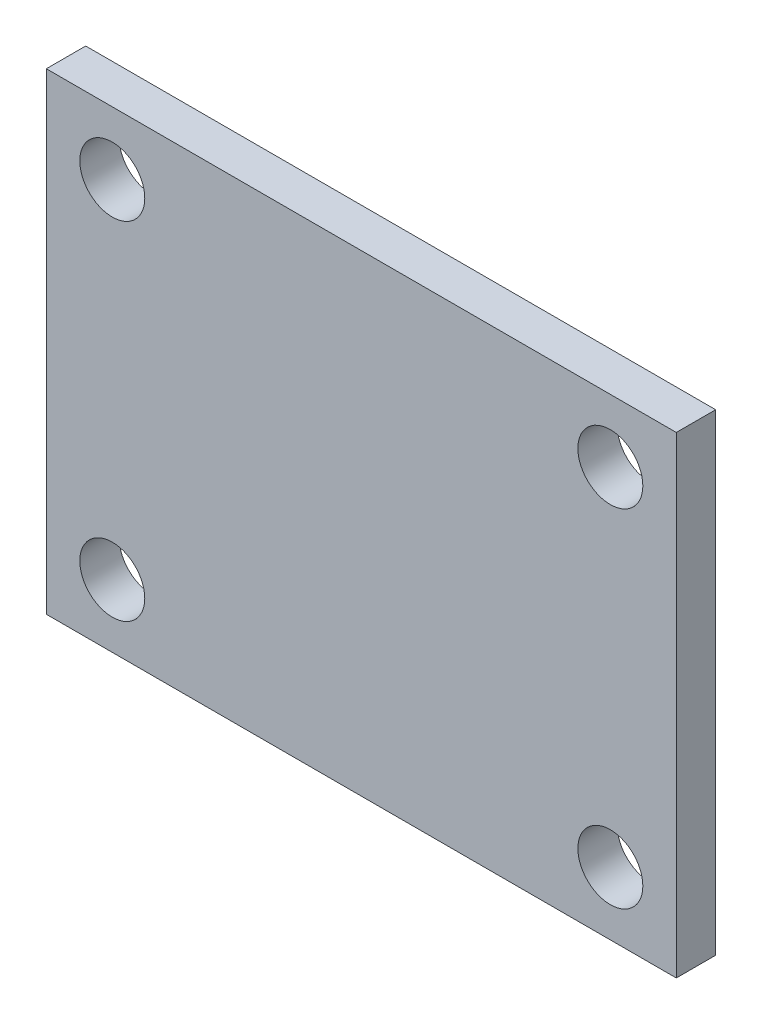
SolidWorks part; units mm, degrees
ref_plane "Front Plane" through (0, 0, 0) normal (0, 0, 1) x (1, 0, 0)
ref_plane "Top Plane" through (0, 0, 0) normal (0, 1, 0) x (1, 0, 0)
ref_plane "Right Plane" through (0, 0, 0) normal (1, 0, 0) x (0, 0, -1)
sketch "Sketch1" plane through (0, 0, 0) normal (0, 0, 1) x (1, 0, 0)
  line L0 (-12.65, 8.8) -> (12.65, 8.8) construction
  line L1 (-16, -12) -> (16, -12)
  line L2 (-16, -12) -> (-16, 12)
  line L3 (-16, 12) -> (16, 12)
  line L4 (16, -12) -> (16, 12)
  line L5 (12.65, 8.8) -> (12.65, -8.8) construction
  line L6 (12.65, -8.8) -> (-12.65, -8.8) construction
  line L7 (-12.65, -8.8) -> (-12.65, 8.8) construction
  circle A0 centre (-12.65, 8.8) radius 1.65
  circle A1 centre (12.65, 8.8) radius 1.65
  circle A2 centre (12.65, -8.8) radius 1.65
  circle A3 centre (-12.65, -8.8) radius 1.65
  point P0 (0, 0)
  dimension "D3" = 3.3
  dimension "D4" = 3.3
  dimension "D5" = 3.3
  dimension "D6" = 3.3
  dimension "D1" = 32
  dimension "D2" = 24
  dimension "D7" = 25.3
  dimension "D8" = 17.6
  dimension "D9" = 8.8
  dimension "D10" = 12.65
extrude "Boss-Extrude1" add sketch "Sketch1" along normal blind 2
equation "\"D4@Sketch1\"=\"D3@Sketch1\""
equation "\"D5@Sketch1\"=\"D3@Sketch1\""
equation "\"D6@Sketch1\"=\"D3@Sketch1\""
equation "\"D9@Sketch1\"=\"D8@Sketch1\"/2"
equation "\"D10@Sketch1\"=\"D7@Sketch1\"/2"
